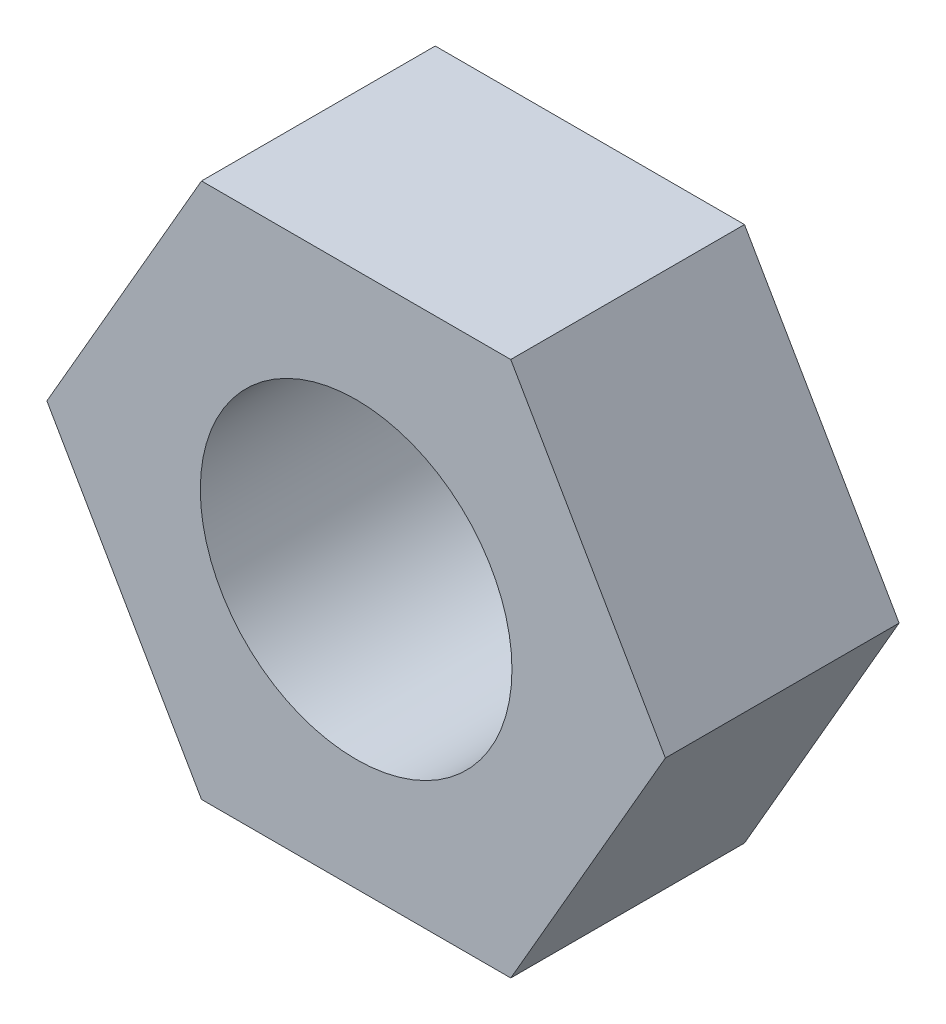
SolidWorks part; units mm, degrees
ref_plane "前视基准面" through (0, 0, 0) normal (0, 0, 1) x (1, 0, 0)
ref_plane "上视基准面" through (0, 0, 0) normal (0, 1, 0) x (1, 0, 0)
ref_plane "右视基准面" through (0, 0, 0) normal (1, 0, 0) x (0, 0, -1)
other "Configuration Table"
sketch "草图1" plane through (0, 0, 0) normal (0, 0, 1) x (1, 0, 0)
  line L1 (3.1754, 0) -> (1.5877, 2.75)
  line L2 (1.5877, 2.75) -> (-1.5877, 2.75)
  line L3 (-1.5877, 2.75) -> (-3.1754, 0)
  line L4 (-3.1754, 0) -> (-1.5877, -2.75)
  line L5 (-1.5877, -2.75) -> (1.5877, -2.75)
  line L6 (1.5877, -2.75) -> (3.1754, 0)
  circle A0 centre (0, 0) radius 2.75 construction
  circle A1 centre (0, 0) radius 1.6
extrude "凸台-拉伸1" add sketch "草图1" along normal mid plane 2.4
